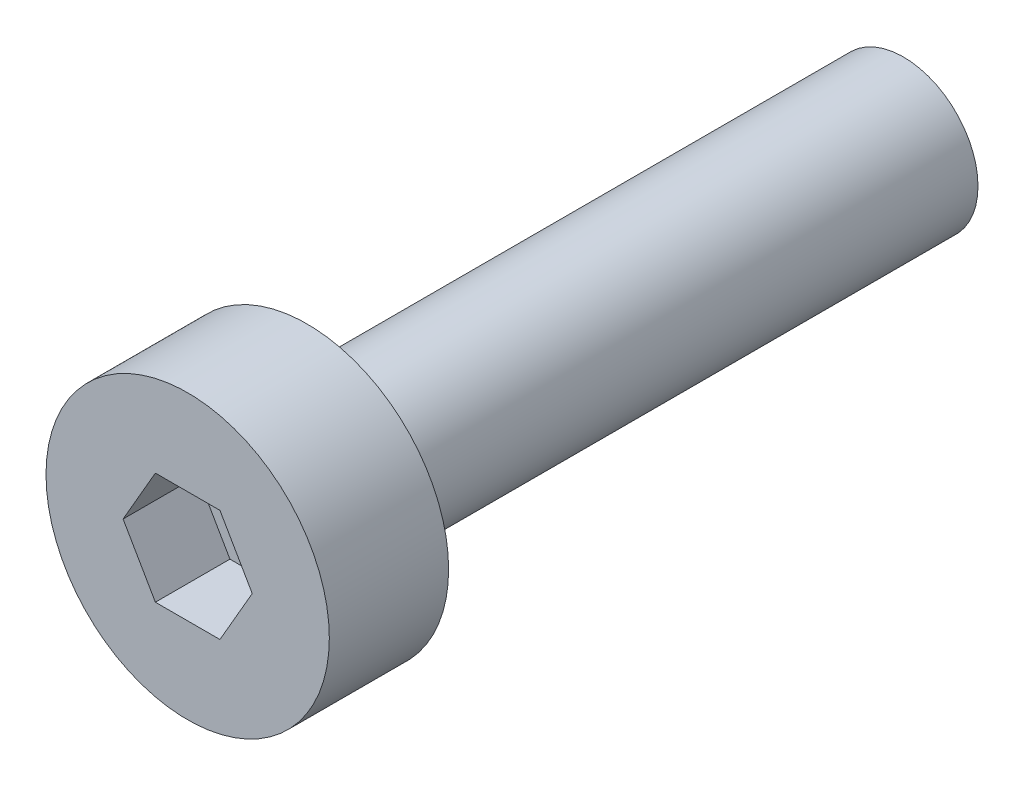
SolidWorks part; units mm, degrees
ref_plane "Plan de face" through (0, 0, 0) normal (0, 0, 1) x (1, 0, 0)
ref_plane "Plan de dessus" through (0, 0, 0) normal (0, 1, 0) x (1, 0, 0)
ref_plane "Plan de droite" through (0, 0, 0) normal (1, 0, 0) x (0, 0, -1)
sketch "Esquisse1" plane through (0, 0, 0) normal (0, 0, 1) x (1, 0, 0)
  circle A0 centre (0, 0) radius 1
  dimension "D1" = 2
extrude "Boss.-Extru.1" add sketch "Esquisse1" along normal blind 8
sketch "Esquisse2" plane through (0, 0, 8) normal (0, 0, 1) x (1, 0, 0)
  circle A0 centre (0, 0) radius 1.9
  dimension "D1" = 3.8
extrude "Boss.-Extru.2" add sketch "Esquisse2" along normal blind 1.6
sketch "Esquisse3" plane through (0, 0, 9.6) normal (0, 0, 1) x (1, 0, 0)
  line L1 (0.866, 0) -> (0.433, 0.75)
  line L2 (0.433, 0.75) -> (-0.433, 0.75)
  line L3 (-0.433, 0.75) -> (-0.866, 0)
  line L4 (-0.866, 0) -> (-0.433, -0.75)
  line L5 (-0.433, -0.75) -> (0.433, -0.75)
  line L6 (0.433, -0.75) -> (0.866, 0)
  circle A0 centre (0, 0) radius 0.75 construction
  dimension "D1" = 1.5
extrude "Enlèv. mat.-Extru.1" cut sketch "Esquisse3" against normal blind 1
